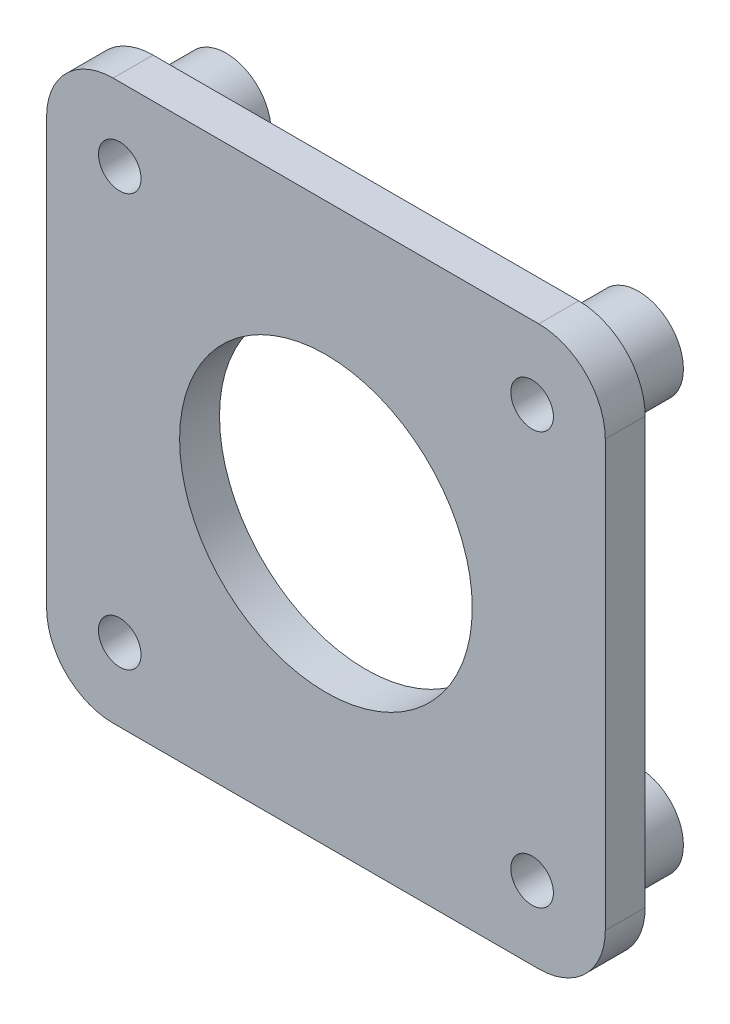
SolidWorks part; units mm, degrees
ref_plane "前视基准面" through (0, 0, 0) normal (0, 0, 1) x (1, 0, 0)
ref_plane "上视基准面" through (0, 0, 0) normal (0, 1, 0) x (1, 0, 0)
ref_plane "右视基准面" through (0, 0, 0) normal (1, 0, 0) x (0, 0, -1)
other "Configuration Table"
sketch "草图1" plane through (0, 0, 0) normal (0, 0, 1) x (1, 0, 0)
  line L1 (-21, -21) -> (21, -21)
  line L2 (-21, -21) -> (-21, 21)
  line L3 (-21, 21) -> (21, 21)
  line L4 (21, -21) -> (21, 21)
  line L5 (-21, -21) -> (21, 21) construction
  line L6 (-21, 21) -> (21, -21) construction
  line L7 (-15.5, -15.5) -> (15.5, -15.5)
  line L8 (-15.5, -15.5) -> (-15.5, 15.5)
  line L9 (-15.5, 15.5) -> (15.5, 15.5)
  line L10 (15.5, -15.5) -> (15.5, 15.5)
  line L11 (-15.5, -15.5) -> (15.5, 15.5) construction
  line L12 (-15.5, 15.5) -> (15.5, -15.5) construction
  circle A0 centre (-15.5, 15.5) radius 1.6
  circle A1 centre (15.5, 15.5) radius 1.6
  circle A2 centre (15.5, -15.5) radius 1.6
  circle A3 centre (-15.5, -15.5) radius 1.6
  circle A4 centre (0, 0) radius 11
  point P0 (0, 0)
  point P6 (0, 0)
  point P21 (0, 0)
  dimension "D4" = 3.2
  dimension "D6" = 22
  dimension "D1" = 42
  dimension "D2" = 42
  dimension "D3" = 31
  dimension "D5" = 4
extrude "凸台-拉伸1" add sketch "草图1" along normal blind 3 contours A3 L7 A2 L10 A1 L9 A0 L8 A4 | L1 L4 L3 L2 A3 L8 A0 L9 A1 L10 A2 L7
fillet "圆角1" radius 5 4 edges at (-21, -21, 1.5) (21, -21, 1.5) (21, 21, 1.5) (-21, 21, 1.5)
sketch "草图2" plane through (0, 0, 0) normal (0, 0, -1) x (-1, 0, 0)
  circle A0 centre (0, 0) radius 16
  circle A1 centre (0, 0) radius 18
  dimension "D1" = 32
  dimension "D2" = 2
extrude "凸台-拉伸2" add sketch "草图2" along normal blind 7
sketch "草图3" plane through (0, 0, 0) normal (0, 0, -1) x (-1, 0, 0)
  circle A0 centre (0, 0) radius 18
extrude "切除-拉伸1" cut sketch "草图3" along normal through all
sketch "草图5" plane through (0, 0, 0) normal (0, 0, -1) x (-1, 0, 0)
  circle A0 centre (-15.5, 15.5) radius 3.3745
  circle A1 centre (-15.5, 15.5) radius 1.6
  circle A2 centre (15.5, 15.5) radius 1.6
  circle A3 centre (15.5, 15.5) radius 3.3745
  circle A4 centre (15.5, -15.5) radius 1.6
  circle A5 centre (15.5, -15.5) radius 3.3745
  circle A6 centre (-15.5, -15.5) radius 1.6
  circle A7 centre (-15.5, -15.5) radius 3.3745
  point P16 (0, 0)
  dimension "D1" = 4
extrude "凸台-拉伸3" add sketch "草图5" along normal blind 10
sketch "草图6" plane through (0, 0, -10) normal (0, 0, -1) x (-1, 0, 0)
  circle A0 centre (0, 0) radius 29.9886
extrude "切除-拉伸2" cut sketch "草图6" against normal blind 5
